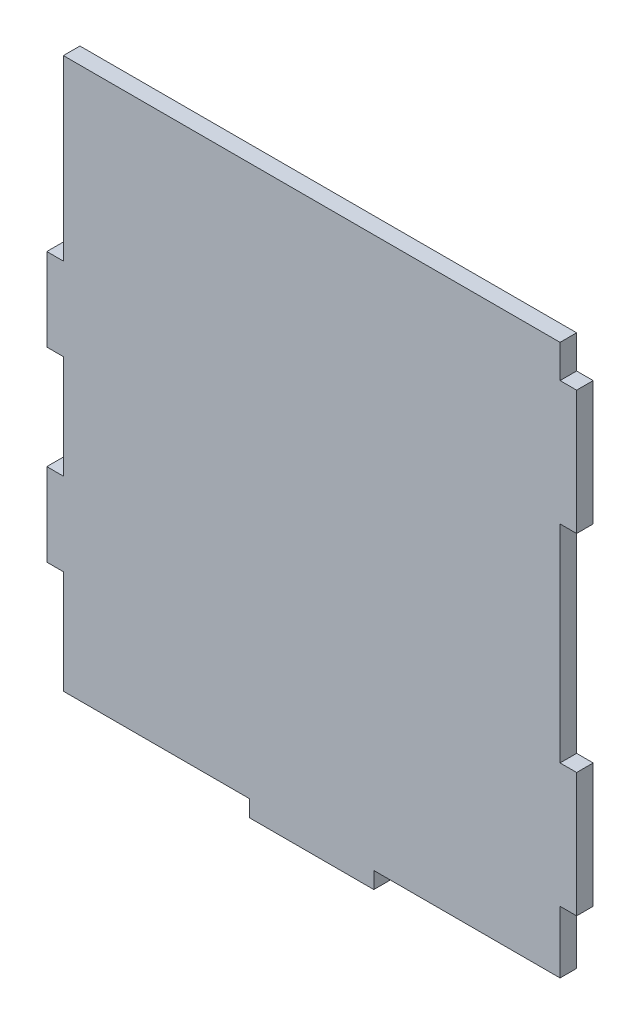
SolidWorks part; units mm, degrees
ref_plane "Спереди" through (0, 0, 0) normal (0, 0, 1) x (1, 0, 0)
ref_plane "Сверху" through (0, 0, 0) normal (0, 1, 0) x (1, 0, 0)
ref_plane "Справа" through (0, 0, 0) normal (1, 0, 0) x (0, 0, -1)
sketch "Эскиз1" plane through (0, 0, 0) normal (0, 0, 1) x (1, 0, 0)
  line L0 (-4, 35) -> (0, 35) construction
  line L1 (0, 0) -> (120, 0)
  line L2 (0, 0) -> (0, 133)
  line L3 (0, 133) -> (120, 133)
  line L4 (120, 0) -> (120, 133)
  line L5 (0, 25) -> (-4, 25)
  line L6 (0, 25) -> (0, 45)
  line L7 (0, 45) -> (-4, 45)
  line L8 (-4, 25) -> (-4, 45)
  line L9 (0, 90) -> (-4, 90)
  line L10 (0, 90) -> (0, 70)
  line L11 (0, 70) -> (-4, 70)
  line L12 (-4, 90) -> (-4, 70)
  line L13 (120, 125) -> (124, 125)
  line L14 (120, 125) -> (120, 95)
  line L15 (120, 95) -> (124, 95)
  line L16 (124, 125) -> (124, 95)
  line L17 (120, 45) -> (124, 45)
  line L18 (120, 45) -> (120, 15)
  line L19 (120, 15) -> (124, 15)
  line L20 (124, 45) -> (124, 15)
  line L21 (-4, 80) -> (0, 80) construction
  line L22 (60, 0) -> (60, -4) construction
  line L23 (45, 0) -> (75, 0)
  line L24 (45, 0) -> (45, -4)
  line L25 (45, -4) -> (75, -4)
  line L26 (75, 0) -> (75, -4)
  line L27 (124, 30) -> (120, 30) construction
  line L28 (124, 110) -> (120, 110) construction
  dimension "D1" = 120
  dimension "D2" = 133
  dimension "D3" = 20
  dimension "D4" = 20
  dimension "D5" = 30
  dimension "D6" = 30
  dimension "D7" = 4
  dimension "D8" = 4
  dimension "D9" = 4
  dimension "D10" = 4
  dimension "D11" = 35
  dimension "D12" = 45
  dimension "D13" = 30
  dimension "D14" = 4
  dimension "D15" = 30
  dimension "D16" = 80
extrude "Бобышка-Вытянуть1" add sketch "Эскиз1" along normal blind 4 contours L1 L4 L3 L2 | L8 L5 L2 L7 | L20 L17 L4 L19 | L16 L13 L4 L15 | L9 L12 L11 L2 | L26 L1 L24 L25
